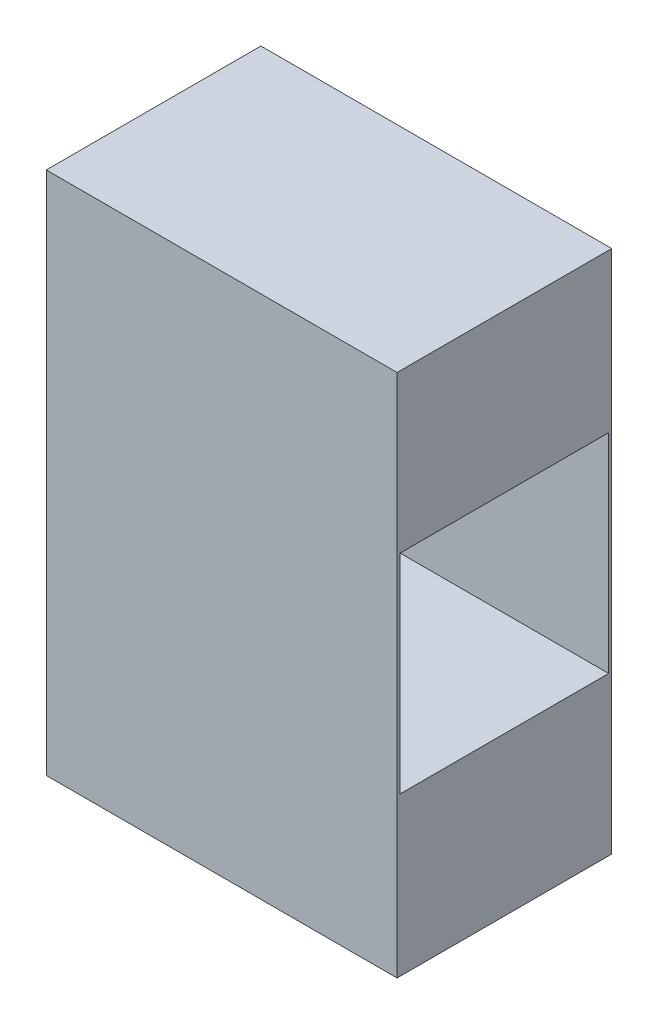
SolidWorks part; units mm, degrees
ref_plane "Front Plane" through (0, 0, 0) normal (0, 0, 1) x (1, 0, 0)
ref_plane "Top Plane" through (0, 0, 0) normal (0, 1, 0) x (1, 0, 0)
ref_plane "Right Plane" through (0, 0, 0) normal (1, 0, 0) x (0, 0, -1)
sketch "Sketch1" plane through (0, 0, 0) normal (0, 1, 0) x (1, 0, 0)
  line L1 (0, 0) -> (29.0576, 0)
  line L2 (0, 0) -> (0, 17.78)
  line L3 (0, 17.78) -> (29.0576, 17.78)
  line L4 (29.0576, 0) -> (29.0576, 17.78)
  dimension "D1" = 17.78
  dimension "D2" = 29.0576
extrude "Boss-Extrude1" add sketch "Sketch1" along normal blind 43.434
sketch "Sketch2" plane through (29.0576, 0, 0) normal (1, 0, 0) x (0, 0, -1)
  line L0 (0, 0) -> (17.78, 0) construction
  line L1 (17.78, 43.434) -> (17.78, 0) construction
  line L3 (17.526, 13.081) -> (0.254, 13.081)
  line L4 (17.526, 13.081) -> (17.526, 30.353)
  line L5 (17.526, 30.353) -> (0.254, 30.353)
  line L6 (0.254, 13.081) -> (0.254, 30.353)
  line L7 (17.526, 13.081) -> (0.254, 30.353) construction
  line L8 (17.526, 30.353) -> (0.254, 13.081) construction
  point P0 (8.89, 21.717)
  dimension "D1" = 17.272
  dimension "D2" = 17.272
  dimension "D3" = 21.717
  dimension "D4" = 8.89
extrude "Cut-Extrude1" cut sketch "Sketch2" against normal blind 25.4
